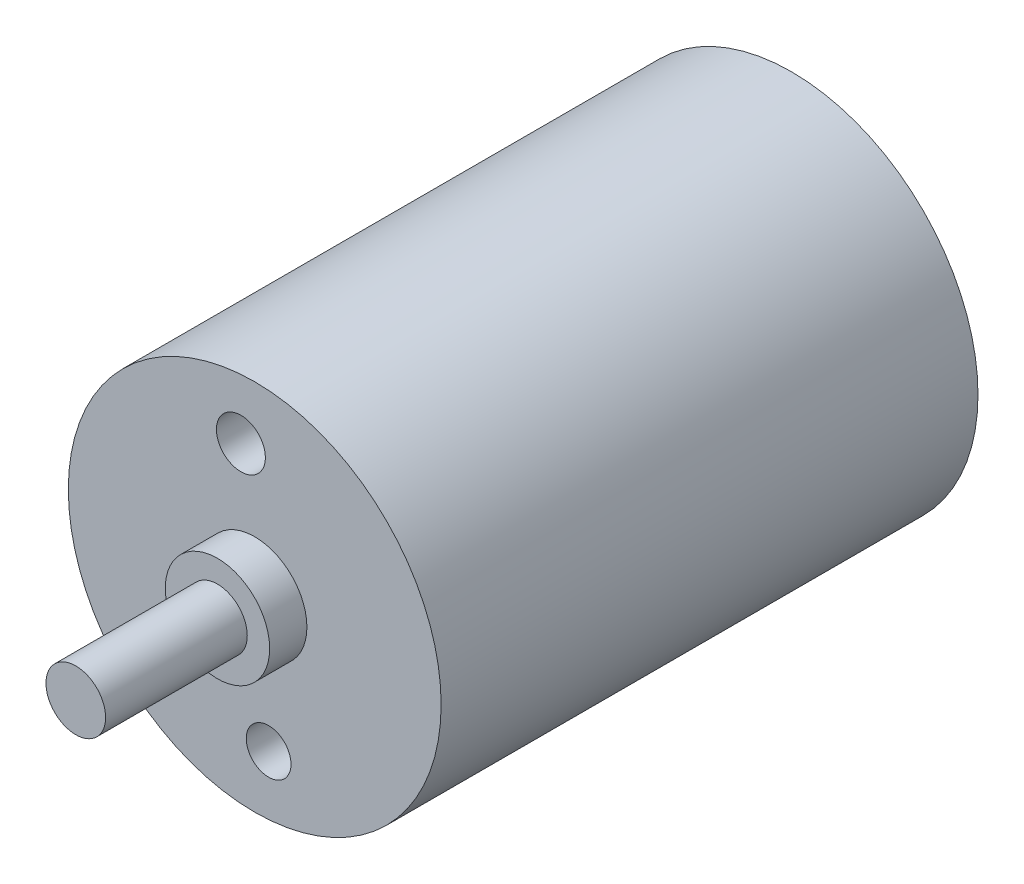
SolidWorks part; units mm, degrees
ref_plane "Front Plane" through (0, 0, 0) normal (0, 0, 1) x (1, 0, 0)
ref_plane "Top Plane" through (0, 0, 0) normal (0, 1, 0) x (1, 0, 0)
ref_plane "Right Plane" through (0, 0, 0) normal (1, 0, 0) x (0, 0, -1)
sketch "Sketch1" plane through (0, 0, 0) normal (0, 0, 1) x (1, 0, 0)
  circle A0 centre (-10.216, 3.5756) radius 12.5
  dimension "D1" = 25
extrude "Boss-Extrude1" add sketch "Sketch1" along normal blind 36 contours A0
sketch "Sketch2" plane through (0, 0, 36) normal (0, 0, 1) x (1, 0, 0)
  circle A0 centre (-10.216, 3.5756) radius 3.5
  circle A1 centre (-10.216, 3.5756) radius 12.5 construction
  dimension "D1" = 0
extrude "Boss-Extrude2" add sketch "Sketch2" along normal blind 2.5
sketch "Sketch3" plane through (0, 0, 38.5) normal (0, 0, 1) x (1, 0, 0)
  circle A0 centre (-10.216, 3.5756) radius 2
  circle A1 centre (-10.216, 3.5756) radius 3.5 construction
  dimension "D1" = 0
extrude "Boss-Extrude3" add sketch "Sketch3" along normal blind 9.5 contours A0
sketch "Sketch4" plane through (0, 0, 36) normal (0, 0, 1) x (1, 0, 0)
  line L0 (-11.1433, 12.0248) -> (-10.216, 3.5756) construction
  line L1 (-11.1433, 12.0248) -> (-10.216, 3.5756) construction
  line L2 (-10.216, 3.5756) -> (-9.283, -4.9244) construction
  circle A0 centre (-11.1433, 12.0248) radius 1.6412
  circle A1 centre (-10.216, 3.5756) radius 2 construction
  circle A2 centre (-9.283, -4.9244) radius 1.5
  dimension "D1" = 8.5
  dimension "D2" = 8.5
extrude "Cut-Extrude1" cut sketch "Sketch4" against normal blind 5
